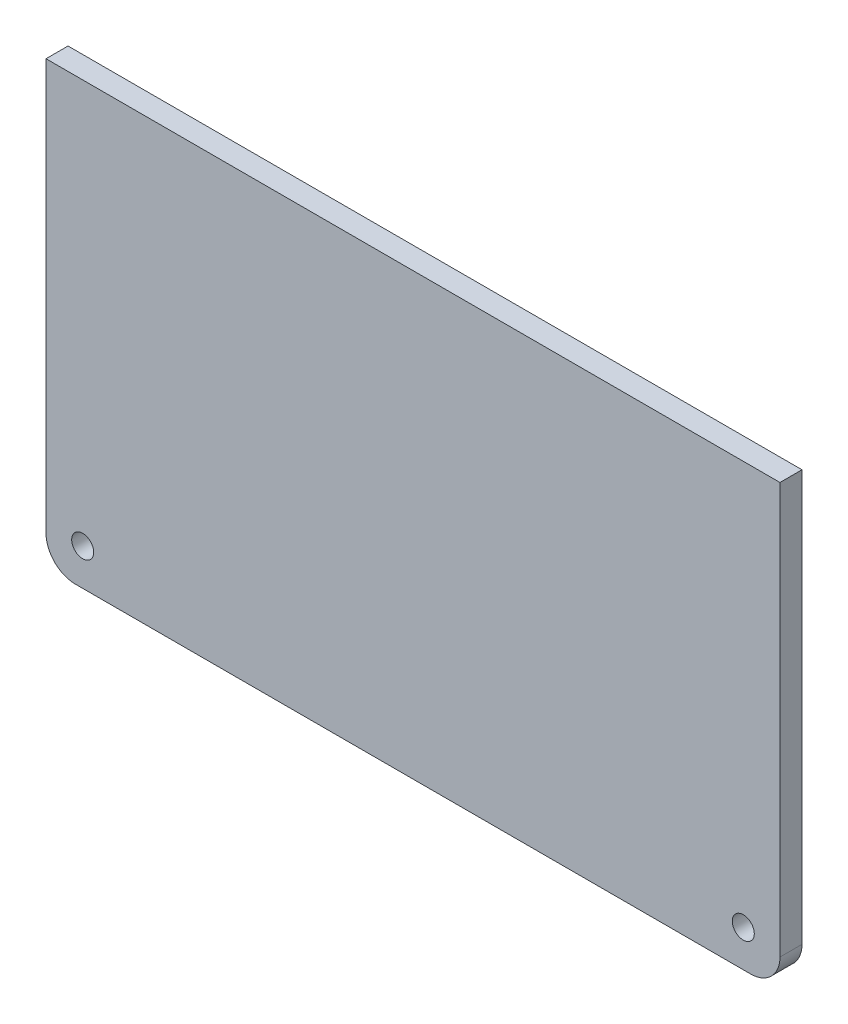
SolidWorks part; units mm, degrees
ref_plane "Front Plane" through (0, 0, 0) normal (0, 0, 1) x (1, 0, 0)
ref_plane "Top Plane" through (0, 0, 0) normal (0, 1, 0) x (1, 0, 0)
ref_plane "Right Plane" through (0, 0, 0) normal (1, 0, 0) x (0, 0, -1)
sketch "Sketch1" plane through (0, 0, 0) normal (0, 0, 1) x (1, 0, 0)
  line L1 (-57.4956, 34.0388) -> (42.5044, 34.0388)
  line L2 (-57.4956, 34.0388) -> (-57.4956, -25.9612)
  line L3 (-57.4956, -25.9612) -> (42.5044, -25.9612)
  line L4 (42.5044, 34.0388) -> (42.5044, -25.9612)
  dimension "D1" = 100
  dimension "D2" = 60
extrude "Boss-Extrude1" add sketch "Sketch1" along normal blind 3
sketch "Sketch2" plane through (0, 0, 3) normal (0, 0, 1) x (1, 0, 0)
  circle A0 centre (37.5044, -20.9612) radius 1.5
  circle A1 centre (-52.5, -20.9612) radius 1.5
extrude "Cut-Extrude1" cut sketch "Sketch2" against normal blind 3
fillet "Fillet1" radius 4 2 edges at (-57.4956, -25.9612, 1.5) (42.5044, -25.9612, 1.5)
